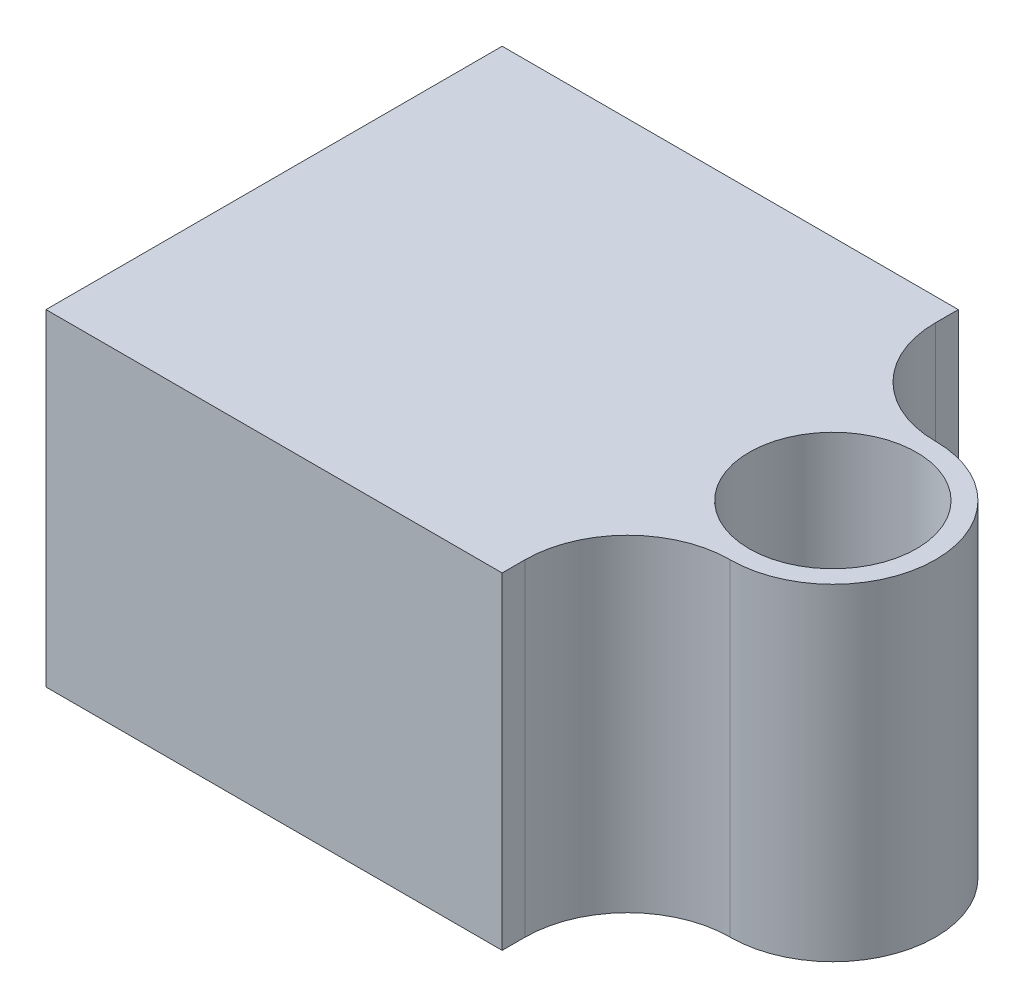
SolidWorks part; units mm, degrees
ref_plane "Спереди" through (0, 0, 0) normal (0, 0, 1) x (1, 0, 0)
ref_plane "Сверху" through (0, 0, 0) normal (0, 1, 0) x (1, 0, 0)
ref_plane "Справа" through (0, 0, 0) normal (1, 0, 0) x (0, 0, -1)
sketch "Эскиз1" plane through (0, 0, 0) normal (0, 1, 0) x (1, 0, 0)
  line L0 (11, 0) -> (13.5, 0)
  line L1 (-13.5, -30) -> (-13.5, 30)
  line L2 (-13.5, 30) -> (-73.5, 30)
  line L3 (-73.5, 30) -> (-73.5, -30)
  line L4 (-73.5, -30) -> (-13.5, -30)
  line L5 (0, -13.5) -> (-13.5, -13.5) construction
  circle A0 centre (0, 0) radius 11
  circle A1 centre (0, 0) radius 13.5
  arc A3 (0, -13.5) -> (-13.5, -27) centre (0, -27) ccw
  arc A5 (-13.5, 27) -> (0, 13.5) centre (0, 27) ccw
  point P9 (-13.5, 0)
extrude "Бобышка-Вытянуть1" add sketch "Эскиз1" along normal mid plane 43
